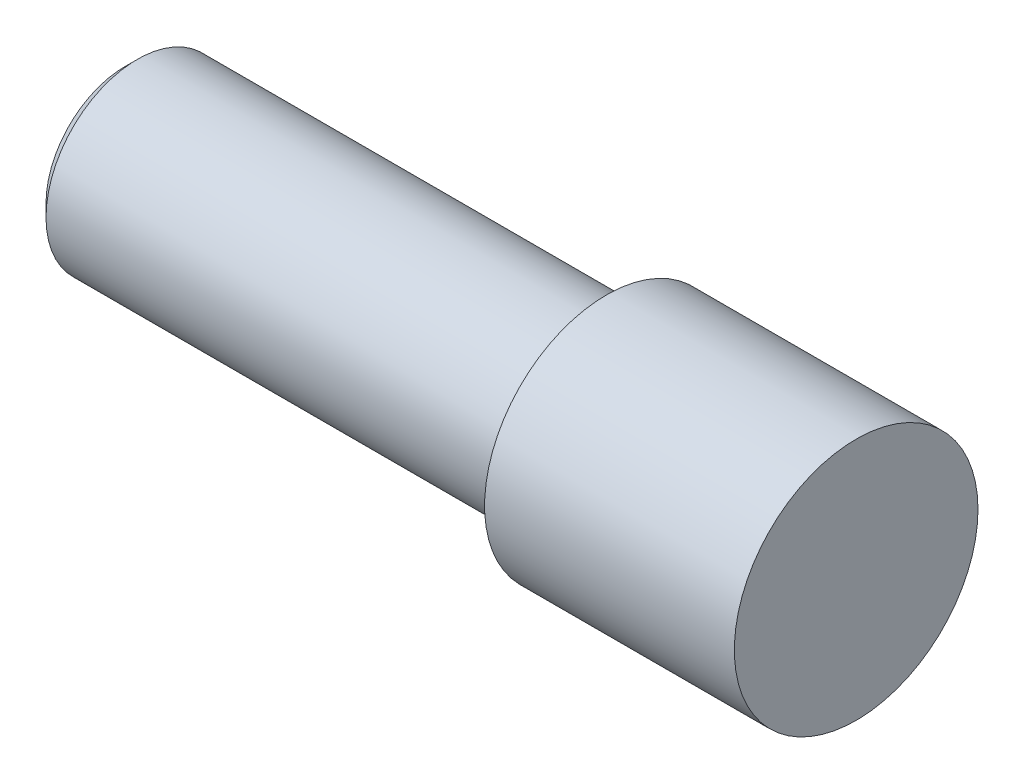
SolidWorks part; units mm, degrees
ref_plane "Front Plane" through (0, 0, 0) normal (0, 0, 1) x (1, 0, 0)
ref_plane "Top Plane" through (0, 0, 0) normal (0, 1, 0) x (1, 0, 0)
ref_plane "Right Plane" through (0, 0, 0) normal (1, 0, 0) x (0, 0, -1)
sketch "Sketch1" plane through (0, 0, 0) normal (1, 0, 0) x (0, 0, -1)
  circle A0 centre (0, 0) radius 2
  dimension "D1" = 4
extrude "Boss-Extrude1" add sketch "Sketch1" along normal blind 4.1
sketch "Sketch2" plane through (0, 0, 0) normal (-1, 0, 0) x (0, 0, 1)
  circle A0 centre (0, 0) radius 1.5
  dimension "D1" = 3
extrude "Boss-Extrude2" add sketch "Sketch2" along normal blind 7.9 contours A0
cosmetic thread "Cosmetic Thread1" parameters "D2"=2.439
chamfer "Chamfer1" distance 0.2 angle 45 1 edges at (-7.9, 0, 1.5)
